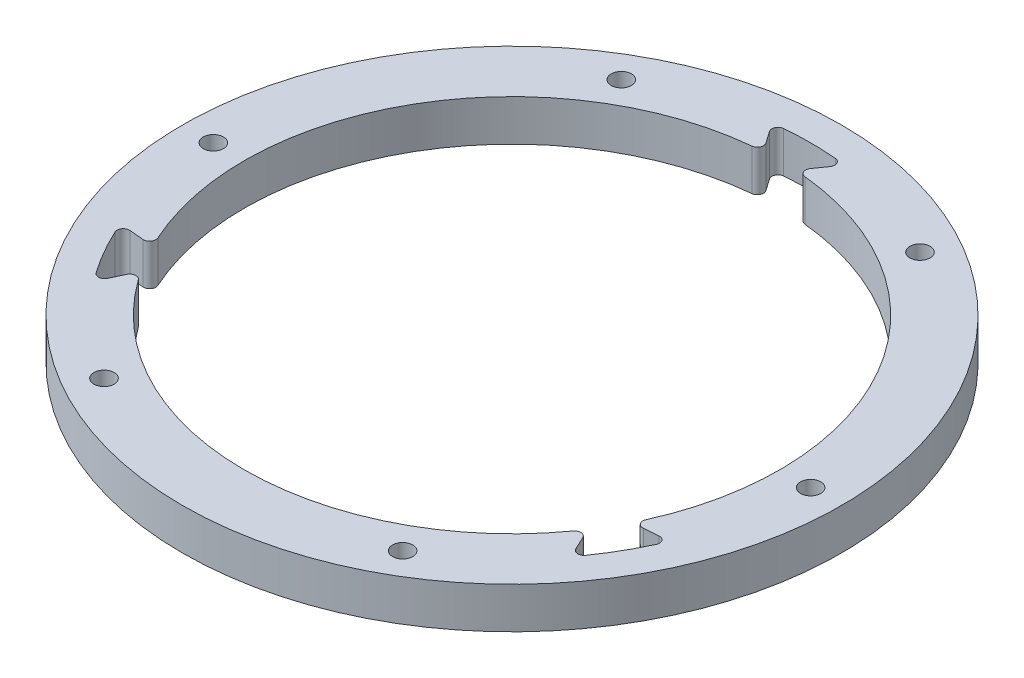
SolidWorks part; units mm, degrees
ref_plane "Front Plane" through (0, 0, 0) normal (0, 0, 1) x (1, 0, 0)
ref_plane "Top Plane" through (0, 0, 0) normal (0, 1, 0) x (1, 0, 0)
ref_plane "Right Plane" through (0, 0, 0) normal (1, 0, 0) x (0, 0, -1)
sketch "Sketch2" plane through (0, 0, 0) normal (1, 0, 0) x (0, 0, -1)
  line L0 (-65, 0) -> (-80, 0)
  line L1 (-80, 0) -> (-80, 10)
  line L2 (-80, 10) -> (-65, 10)
  line L5 (-65, 10) -> (-65, 0)
  dimension "D1" = 80
  dimension "D2" = 10
  dimension "D4" = 15
ref_axis "Axis1" through (0, -0.75, 0) along (0, 1, 0)
revolve "Revolve1" add sketch "Sketch2" angle 360 about axis through (0, -0.75, 0) along (0, 1, 0)
sketch "Sketch4" plane through (0, 10, 0) normal (0, 1, 0) x (1, 0, 0)
  line L0 (0, 0) -> (0, 84.4218) construction
  line L1 (-3.8812, 64.884) -> (-8.8355, 71.9596)
  line L2 (8.8355, 71.9596) -> (3.8812, 64.884)
  line L3 (-3.8812, 64.884) -> (0, 59.3412) construction
  line L4 (0, 0) -> (-8.8355, 71.9596) construction
  arc A0 (-3.8812, 64.884) -> (3.8812, 64.884) centre (0, 0) cw
  arc A2 (-8.8355, 71.9596) -> (8.8355, 71.9596) centre (0, 0) cw
  circle A3 centre (0, 0) radius 65 construction
  dimension "D1" = 35
  dimension "D2" = 7.5
  dimension "D3" = 7
  dimension "D4" = 130
extrude "Cut-Extrude1" cut sketch "Sketch4" against normal through all
fillet "Fillet1" radius 1.5 4 edges at (8.8355, 5, -71.9596) (-8.8355, 5, -71.9596) (3.8812, 5, -64.884) (-3.8812, 5, -64.884)
pattern_circular "CirPattern2" count 3 over 360 about axis through (0, 0, 0) along (0, 1, 0) of "Cut-Extrude1", "Fillet1"
hole_wizard "#10 (0.1935) Diameter Hole1" positions "Sketch6" profile "Sketch7" hole size "#10" standard "ANSI Inch" end condition through all
sketch "Sketch6" plane through (0, 10, 0) normal (0, 1, 0) x (1, 0, 0)
  line L0 (0, 0) -> (-69.8201, 120.932) construction
  line L2 (0, 0) -> (0, 109.0908) construction
  point P0 (-36.25, 62.7868)
  dimension "D1" = 30
  dimension "D2" = 72.5
sketch "Sketch7" plane through (-36.25, 10, -62.7868) normal (1, 0, 0) x (0, 0, 1)
  line L0 (0, 0) -> (0, 10)
  line L1 (0, 10) -> (2.4574, 10)
  line L2 (2.4574, 10) -> (2.4574, 0)
  line L5 (2.4574, 0) -> (0, 0)
  line L11 (0, -6.35) -> (0, 107.95) construction
  dimension "Thru Hole Dia." = 4.9149
  dimension "Thru Hole Depth" = 10
pattern_circular "CirPattern3" count 6 over 360 about axis through (0, 0, 0) along (0, 1, 0) of "#10 (0.1935) Diameter Hole1"
